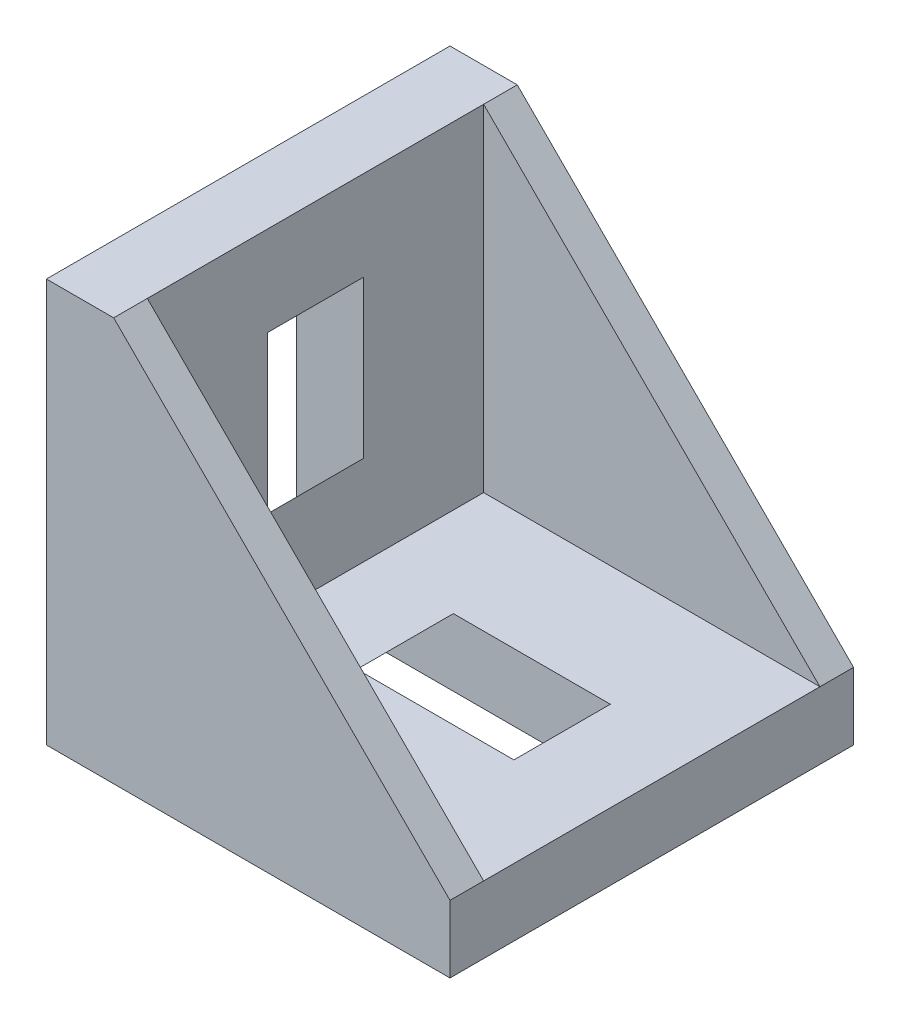
SolidWorks part; units mm, degrees
ref_plane "Front Plane" through (0, 0, 0) normal (0, 0, 1) x (1, 0, 0)
ref_plane "Top Plane" through (0, 0, 0) normal (0, 1, 0) x (1, 0, 0)
ref_plane "Right Plane" through (0, 0, 0) normal (1, 0, 0) x (0, 0, -1)
sketch "Sketch1" plane through (0, 0, 0) normal (0, 0, 1) x (1, 0, 0)
  line L0 (0, 0) -> (0, 18)
  line L1 (18, 3) -> (3, 18)
  line L4 (3, 18) -> (0, 18)
  line L5 (18, 0) -> (0, 0)
  line L7 (18, 3) -> (18, 0)
  dimension "D" = 3
  dimension "C" = 18
  dimension "B" = 18
extrude "Boss-Extrude1" add sketch "Sketch1" along normal mid plane 18
sketch "Sketch2" plane through (0, 0, 0) normal (0, 0, 1) x (1, 0, 0)
  line L0 (3, 18) -> (3, 3)
  line L1 (3, 3) -> (18, 3)
  line L2 (3, 18) -> (18, 3)
extrude "Cut-Extrude1" cut sketch "Sketch2" against normal mid plane 15
sketch "Sketch3" plane through (0, 0, 0) normal (0, 0, 1) x (1, 0, 0)
  line L0 (18, 3) -> (3, 18) construction
  line L1 (0, 14) -> (3, 14)
  line L2 (0, 14) -> (0, 4)
  line L3 (0, 4) -> (3, 7)
  line L4 (3, 14) -> (3, 7)
  line L5 (7, 3) -> (14, 3)
  line L6 (7, 3) -> (4, 0)
  line L7 (4, 0) -> (14, 0)
  line L8 (14, 3) -> (14, 0)
  line L9 (3, 18) -> (0, 18) construction
  line L10 (18, 0) -> (0, 0) construction
  line L11 (0, 0) -> (0, 18) construction
  line L12 (18, 0) -> (18, 3) construction
  dimension "D1" = 14
  dimension "D2" = 7
  dimension "D3" = 14
  dimension "D4" = 7
  dimension "D5" = 4
  dimension "D6" = 4
extrude "Cut-Extrude2" cut sketch "Sketch3" against normal mid plane 4.3
sketch "Sketch4" plane through (0, 0, 0) normal (0, 0, 1) x (1, 0, 0)
  line L0 (0, 18) -> (0, 0) construction
  line L1 (1.2115, 2.3429) -> (0, 1.2348) construction
  line L2 (1.5046, -1.8) -> (0.5112, -0.7909)
  line L3 (0, 3.5355) -> (-1.8, 1.5046)
  line L4 (-1.8, 1.5046) -> (-0.7909, 0.5112)
  line L5 (-0.7909, 0.5112) -> (0, 1.2348)
  line L6 (0, 1.2348) -> (0, 3.5355)
  line L7 (0.5112, -0.7909) -> (1.2348, 0)
  line L8 (0, 0) -> (0, 18) construction
  line L9 (-1.2955, 1.0079) -> (0, 2.3239) construction
  line L10 (1.2348, 0) -> (3.5355, 0)
  line L11 (3.5355, 0) -> (1.5046, -1.8)
  line L12 (0, 17.3) -> (0, 14.9992)
  line L13 (0, 14.9992) -> (-0.7909, 14.2757)
  line L14 (-0.7909, 14.2757) -> (-1.8, 15.269)
  line L15 (-1.8, 15.269) -> (0, 17.3)
  line L16 (-1.2955, 14.7724) -> (0, 16.0884) construction
  line L17 (0, 16.0884) -> (0.6057, 16.7037) construction
  line L18 (18, 3) -> (3, 18) construction
  line L19 (10.5, 10.5) -> (0, 0) construction
  line L20 (0, 17.3) -> (1.2115, 16.1074) construction
  line L21 (0, 14.9992) -> (1.2115, 16.1074) construction
  line L22 (0, 3.5355) -> (1.2115, 2.3429) construction
  line L23 (14.9992, 0) -> (14.2757, -0.7909)
  line L24 (0.6057, 2.9392) -> (0, 2.3239) construction
  line L25 (14.2757, -0.7909) -> (15.269, -1.8)
  line L26 (17.3, 0) -> (14.9992, 0)
  line L27 (15.269, -1.8) -> (17.3, 0)
  line L28 (-1.8, 1.5046) -> (-1.8, 15.269) construction
  dimension "D1" = 1.7
  dimension "D2" = 5
  dimension "D3" = 6
  dimension "D4" = 1.6001
  dimension "D5" = 0.7
  dimension "D6" = 0.1905
  dimension "D7" = 1.8
extrude "Boss-Extrude2" add sketch "Sketch4" along normal mid plane 5
extrude "Cut-Extrude6" cut sketch "Sketch8" against normal blind 2.54 contours L6 L9 L8 L7
sketch "Sketch8" plane through (114.3, 0, -271.0002) normal (0, 1, 0) x (0, 0, 1)
  line L1 (236.6608, -203.2) -> (236.6608, 152.4)
  line L6 (268.8502, -100.3) -> (268.8502, -107.3)
  line L7 (268.8502, -100.3) -> (273.1502, -100.3)
  line L8 (273.1502, -100.3) -> (273.1502, -107.3)
  line L9 (268.8502, -107.3) -> (273.1502, -107.3)
